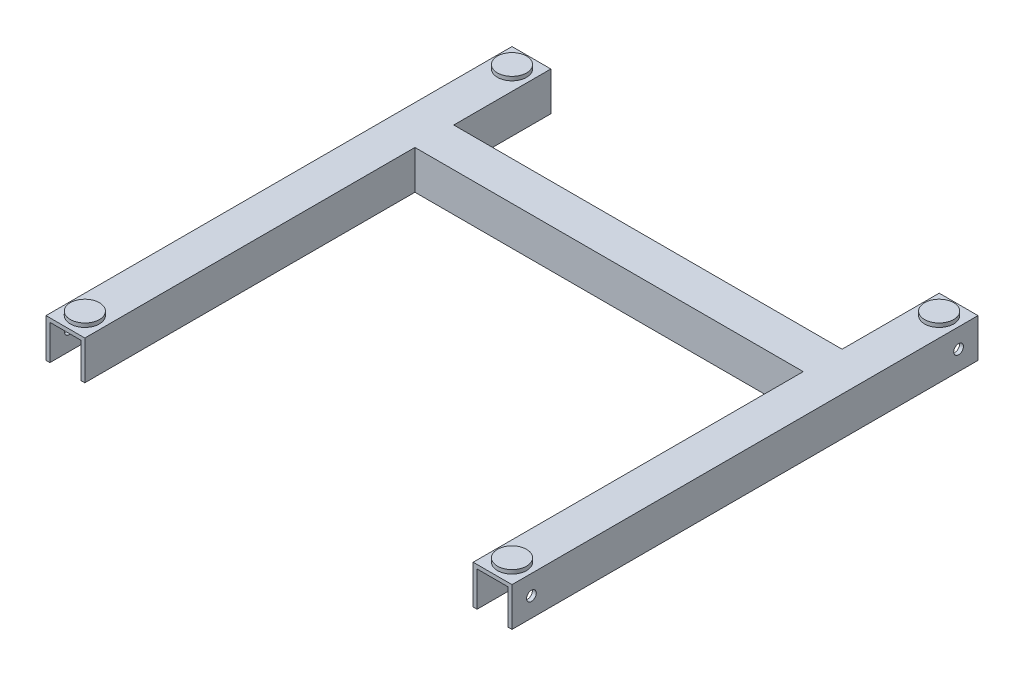
SolidWorks part; units mm, degrees
ref_plane "Front Plane" through (0, 0, 0) normal (0, 0, 1) x (1, 0, 0)
ref_plane "Top Plane" through (0, 0, 0) normal (0, 1, 0) x (1, 0, 0)
ref_plane "Right Plane" through (0, 0, 0) normal (1, 0, 0) x (0, 0, -1)
sketch "Sketch1" plane through (0, 0, 0) normal (0, 1, 0) x (1, 0, 0)
  line L1 (0, 0) -> (25.4, 0)
  line L2 (0, 0) -> (0, 304.8)
  line L3 (0, 304.8) -> (25.4, 304.8)
  line L4 (25.4, 0) -> (25.4, 304.8)
  dimension "D1" = 25.4
  dimension "D2" = 304.8
extrude "Boss-Extrude1" add sketch "Sketch1" along normal blind 25.4
sketch "Sketch2" plane through (0, 0, 0) normal (0, 0, 1) x (1, 0, 0)
  line L0 (0, 0) -> (25.4, 0) construction
  line L1 (2.54, 0) -> (22.86, 0)
  line L2 (2.54, 0) -> (2.54, 22.86)
  line L3 (2.54, 22.86) -> (22.86, 22.86)
  line L4 (22.86, 0) -> (22.86, 22.86)
  line L5 (25.4, 25.4) -> (25.4, 0) construction
  line L6 (0, 25.4) -> (0, 0) construction
  line L7 (0, 25.4) -> (25.4, 25.4) construction
  dimension "D1" = 2.54
  dimension "D2" = 2.54
  dimension "D3" = 2.54
extrude "Cut-Extrude1" cut sketch "Sketch2" against normal through all
sketch "Sketch3" plane through (0, 25.4, 0) normal (0, 1, 0) x (1, 0, 0)
  line L0 (25.4, 0) -> (25.4, 304.8) construction
  line L1 (0, 0) -> (25.4, 0) construction
  line L2 (25.4, 304.8) -> (0, 304.8) construction
  line L3 (0, 304.8) -> (0, 0) construction
  circle A0 centre (12.7, 12.7) radius 9.525
  circle A1 centre (12.7, 292.1) radius 9.525
  point P12 (-84.0445, 316.5459)
  dimension "D1" = 19.05
  dimension "D2" = 12.7
  dimension "D4" = 19.05
  dimension "D3" = 12.7
  dimension "D5" = 12.7
  dimension "D6" = 12.7
extrude "Boss-Extrude2" add sketch "Sketch3" along normal blind 2.54
sketch "Sketch4" plane through (25.4, 0, 0) normal (1, 0, 0) x (0, 0, -1)
  line L0 (0, 0) -> (304.8, 0) construction
  line L1 (215.9, 0) -> (241.3, 0)
  line L2 (215.9, 0) -> (215.9, 25.4)
  line L3 (215.9, 25.4) -> (241.3, 25.4)
  line L4 (241.3, 0) -> (241.3, 25.4)
  line L5 (0, 25.4) -> (304.8, 25.4) construction
  line L6 (304.8, 25.4) -> (304.8, 0) construction
  dimension "D1" = 63.5
  dimension "1" = 25.4
extrude "Boss-Extrude3" add sketch "Sketch4" along normal blind 127
sketch "Sketch5" plane through (152.4, 0, 0) normal (1, 0, 0) x (0, 0, -1)
  line L0 (215.9, 0) -> (241.3, 0) construction
  line L1 (218.44, 0) -> (238.76, 0)
  line L2 (218.44, 0) -> (218.44, 22.86)
  line L3 (218.44, 22.86) -> (238.76, 22.86)
  line L4 (238.76, 0) -> (238.76, 22.86)
  line L5 (241.3, 0) -> (241.3, 25.4) construction
  line L6 (215.9, 25.4) -> (215.9, 0) construction
  line L7 (241.3, 25.4) -> (215.9, 25.4) construction
  dimension "D1" = 2.54
  dimension "D2" = 2.54
  dimension "D3" = 2.54
extrude "Cut-Extrude2" cut sketch "Sketch5" against normal blind 127
mirror "Mirror5" about plane through (152.4, 0, 0) normal (-1, 0, 0) of bodies 105
sketch "Sketch6" plane through (304.8, 0, 0) normal (1, 0, 0) x (0, 0, -1)
  line L0 (0, 25.4) -> (0, 0) construction
  line L1 (304.8, 0) -> (0, 0) construction
  line L2 (304.8, 25.4) -> (304.8, 0) construction
  line L3 (304.8, 25.4) -> (0, 25.4) construction
  circle A0 centre (12.7, 12.7) radius 3.175
  circle A1 centre (292.1, 12.7) radius 3.175
  dimension "D1" = 6.35
  dimension "D4" = 6.35
  dimension "D2" = 12.7
  dimension "D3" = 12.7
  dimension "D5" = 12.7
  dimension "D6" = 12.7
extrude "Cut-Extrude3" cut sketch "Sketch6" against normal blind 12.7
sketch "Sketch7" plane through (0, 0, 0) normal (-1, 0, 0) x (0, 0, 1)
  line L0 (-304.8, 25.4) -> (-304.8, 0) construction
  line L1 (-304.8, 0) -> (0, 0) construction
  line L2 (0, 25.4) -> (0, 0) construction
  circle A0 centre (-292.1, 12.7) radius 3.175
  circle A1 centre (-12.7, 12.7) radius 3.175
  dimension "D1" = 6.35
  dimension "D4" = 6.35
  dimension "D2" = 12.7
  dimension "D3" = 12.7
  dimension "D5" = 12.7
  dimension "D6" = 12.7
extrude "Cut-Extrude4" cut sketch "Sketch7" against normal blind 12.7
